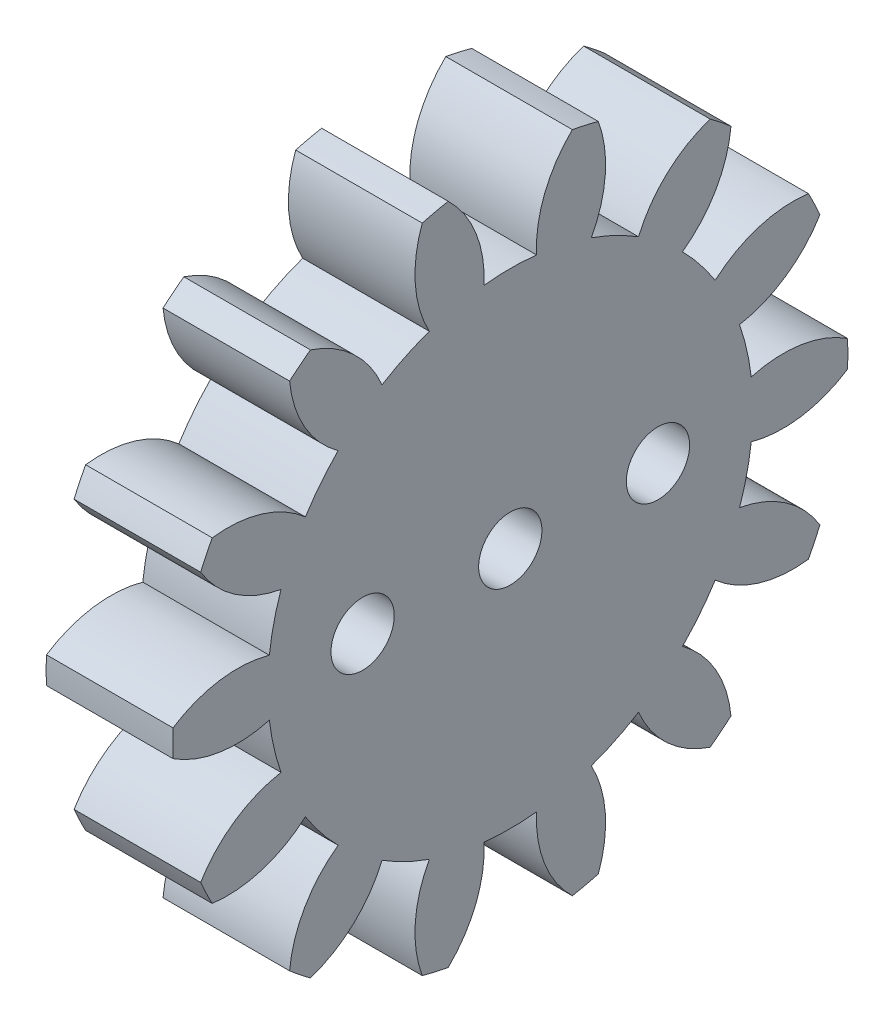
SolidWorks part; units mm, degrees
ref_plane "Plane1" through (0, 0, 0) normal (0, 0, 1) x (1, 0, 0)
ref_plane "Plane2" through (0, 0, 0) normal (0, 1, 0) x (1, 0, 0)
ref_plane "Plane3" through (0, 0, 0) normal (1, 0, 0) x (0, 0, -1)
sketch "HoldingSke" plane through (0, 0, 0) normal (0, 1, 0) x (1, 0, 0)
  line L0 (0, 0) -> (0.4851, -0.121)
  line L1 (-15, 0) -> (100, 0) construction
  line L2 (0, 0) -> (-2.1039, 2.3779)
  line L3 (0, 0) -> (-11.863, 4.5341)
  line L4 (0, 0) -> (8.3795, 2.0892)
  line L5 (0, 0) -> (-46.8476, -17.4728)
  line L6 (0, 0) -> (-4.9738, -3.3558)
  line L7 (-2.1039, 2.3779) -> (8.6586, 51.2059)
  line L8 (-76.2, 54.61) -> (-74.8, 54.61)
  line L9 (-67.7845, 28.3722) -> (-49.3413, 33.142)
  line L10 (-76.2, 71.12) -> (104.1128, 71.12)
  line L11 (0, 0) -> (-6, 0)
  line L12 (-76.2, 101.6) -> (-76.133, 101.6)
  line L13 (24.9733, 27.94) -> (52.9518, 28.4284)
  line L14 (24.9733, 27.94) -> (24.9743, 27.94)
  line L15 (24.9733, 27.94) -> (100.4006, 29.5858)
  line L16 (-63.627, -2) -> (-12.827, -2)
  circle A0 centre (0, 0) radius 4
  circle A1 centre (0, 0) radius 11.499
  circle A2 centre (0, 0) radius 37.5
  circle A3 centre (0, 0) radius 4
  dimension "MHD" = 22.998
  dimension "Hub_dia" = 75
  dimension "Bore" = 8
  dimension "MBD" = 8
  dimension "Num_teeth" = 14
  dimension "Pitch" = 0.5
  dimension "Overall_len" = 50
  dimension "Show_teeth" = 14
  dimension "Thickness" = 6
  dimension "OAL" = 50.0001
  dimension "T_dim" = 1.4
  dimension "Ap" = 14.5
  dimension "H" = 19.05
  dimension "Pitch_radius" = 180.3128
  dimension "Width" = 6
  dimension "Backlash" = 0.067
  dimension "Addendum_fac" = 1
  dimension "Dedendum_fac" = 1.25
  dimension "Clearance_fac" = 0.25
  dimension "Dedendum_add" = 0.001
  dimension "Module" = 2
sketch "BasProSke" plane through (0, 0, 0) normal (0, 1, 0) x (1, 0, 0)
  line L0 (-10, 0) -> (60, 0) construction
  line L1 (0, 0) -> (0, 16)
  line L2 (0, 0) -> (6, 0)
  line L3 (6, 0) -> (6, 16)
  line L4 (6, 16) -> (0, 16)
  dimension "Thickness" = 6
  dimension "Diameter" = 32
revolve "Base-Revolve" add sketch "BasProSke" angle 360 about L0
sketch "TooCutSke" plane through (0, 0, 0) normal (1, 0, 0) x (0, 0, -1)
  line L1 (0, 0) -> (0, 107) construction
  line L2 (0, 0) -> (-1.6846, 13.8983) construction
  line L3 (0, 0) -> (-6.1971, 27.1511) construction
  line L4 (-1.6846, 13.8983) -> (-3.0985, 13.5756) construction
  arc A0 (1.2433, 11.4316) -> (-1.2433, 11.4316) centre (0, 0) ccw
  arc A1 (2.9643, 15.7489) -> (-2.9643, 15.7489) centre (0, 0) ccw
  circle A2 centre (0, 0) radius 14 construction
  circle A3 centre (0, 0) radius 13.5541 construction
  arc A4 (-1.2433, 11.4316) -> (-2.9643, 15.7489) centre (-6.8366, 11.7035) ccw
  arc A5 (2.9643, 15.7489) -> (1.2433, 11.4316) centre (6.8366, 11.7035) ccw
  dimension "Root_dia" = 22.998
  dimension "Overcut_dia" = 32.0508
  dimension "Pitch_dia" = 28
  dimension "Base_dia" = 27.1081
  dimension "Flank_rad" = 5.6
  dimension "Half_ang" = 12.857
  dimension "Half_CT" = 1.4503
extrude "ToothCut" cut sketch "TooCutSke" along normal through all
fillet "Breaks" [suppressed] radius 0.04
fillet "RootFillets" [suppressed] radius 0.501
pattern_circular "TeethCuts" count 14 every 25.714 about axis through (-10, 0, 0) along (1, 0, 0) of "ToothCut", "RootFillets", "Breaks"
sketch "HubNeaOneSke" plane through (0, 0, 0) normal (-1, 0, 0) x (0, 0, 1)
  circle A0 centre (0, 0) radius 11.499
  dimension "Diameter" = 22.998
extrude "HubNearOne" [suppressed] add sketch "HubNeaOneSke" along normal blind 44.0001
sketch "HubNeaBotSke" plane through (0, 0, 0) normal (-1, 0, 0) x (0, 0, 1)
  circle A0 centre (0, 0) radius 11.499
  dimension "Diameter" = 22.998
extrude "HubNearBoth" [suppressed] add sketch "HubNeaBotSke" along normal blind 22
ref_plane "FarPln" through (6, 0, 0) normal (1, 0, 0) x (0, 0, -1)
sketch "HubFarSke" plane through (6, 0, 0) normal (1, 0, 0) x (0, 0, -1)
  circle A0 centre (0, 0) radius 11.499
  dimension "Diameter" = 22.998
extrude "HubFar" [suppressed] add sketch "HubFarSke" along normal blind 22
sketch "BorSke" plane through (0, 0, 0) normal (1, 0, 0) x (0, 0, -1)
  circle A0 centre (0, 0) radius 4
  dimension "Diameter" = 8
extrude "Bore" cut sketch "BorSke" along normal mid plane 100.0001
sketch "KeySke" plane through (0, 0, 0) normal (1, 0, 0) x (0, 0, -1)
  line L0 (-1.5, 0) -> (-1.5, 5.4)
  line L1 (-1.5, 5.4) -> (1.5, 5.4)
  line L2 (1.5, 5.4) -> (1.5, 0)
  line L3 (0, 0) -> (0, 34) construction
  line L4 (-1.5, 0) -> (1.5, 0)
  dimension "Offset" = 5.4
  dimension "Width" = 3
extrude "Keyway" [suppressed] cut sketch "KeySke" along normal mid plane 100.0001
pattern_circular "Keyway2" [suppressed] count 2 every 90 about axis through (-10, 0, 0) along (1, 0, 0)
sketch "Croquis1" plane through (6, 0, 0) normal (1, 0, 0) x (0, 0, -1)
  circle A0 centre (0, 0) radius 4
  circle A1 centre (0, 0) radius 1.5
extrude "Saliente-Extruir1" add sketch "Croquis1" against normal blind 6
sketch "Croquis2" plane through (6, 0, 0) normal (1, 0, 0) x (0, 0, -1)
  circle A0 centre (-7, 0) radius 1.5
  circle A1 centre (7, 0) radius 1.5
  circle A2 centre (0, 0) radius 1.5 construction
  dimension "D1" = 7
  dimension "D2" = 7
extrude "Cortar-Extruir1" cut sketch "Croquis2" against normal blind 6
equation "' \"Module@HoldingSke\" = 6.35"
equation "' \"Num_teeth@HoldingSke\" = 12"
equation "' \"Ap@HoldingSke\" =  20"
equation "' \"Ap@HoldingSke\" = 20"
equation "' \"Width@HoldingSke\" = 0.5 * 25.4"
equation "' \"Hub_dia@HoldingSke\"= 1 * 25.4"
equation "' \"Hub_dia@HoldingSke\" = 1 * 25.4"
equation "' \"Overall_len@HoldingSke\" = 1.0 * 25.4"
equation "' \"Bore@HoldingSke\" = 0.75 * 25.4"
equation "' \"T_dim@HoldingSke\" = 0.1 * 25.4"
equation "' \"Width@KeySke\" = 0.25 * 25.4"
equation "' \"Show_teeth@HoldingSke\" = 13"
equation "' \"Backlash@HoldingSke\" = 0.009 * 25.4"
equation "' \"Addendum_fac@HoldingSke\" = 1.0"
equation "' \"Dedendum_fac@HoldingSke\" = 1.25"
equation "' \"Dedendum_add@HoldingSke\" = 0.00005 * 25.4"
equation "' \"Clearance_fac@HoldingSke\" = 0.25"
equation "\"Pitch@HoldingSke\" = 1 / \"Module@HoldingSke\""
equation "\"Overcut_dia@TooCutSke\" = (\"Num_teeth@HoldingSke\" + 2 * \"Addendum_fac@HoldingSke\") / \"Pitch@HoldingSke\" + 0.002 * 25.4"
equation "\"Pitch_dia@TooCutSke\" = \"Num_teeth@HoldingSke\" / \"Pitch@HoldingSke\""
equation "\"Base_dia@TooCutSke\" = \"Num_teeth@HoldingSke\" / \"Pitch@HoldingSke\" * cos((\"Ap@HoldingSke\"  * 3.14159265 / 180))"
equation "\"Root_dia@TooCutSke\" = (\"Num_teeth@HoldingSke\" + 2) / \"Pitch@HoldingSke\" - 2 * (\"Addendum_fac@HoldingSke\" + \"Dedendum_fac@HoldingSke\") / \"Pitch@HoldingSke\" - \"Dedendum_add@HoldingSke\" * 2"
equation "\"Half_ang@TooCutSke\" = 180 / \"Num_teeth@HoldingSke\""
equation "\"Half_CT@TooCutSke\" = \"Num_teeth@HoldingSke\" / \"Pitch@HoldingSke\" * sin((3.14159265 / 2 / \"Num_teeth@HoldingSke\")) / 2 - 7 * \"Backlash@HoldingSke\" / 4"
equation "\"Flank_rad@TooCutSke\" = \"Num_teeth@HoldingSke\" / \"Pitch@HoldingSke\" / 5"
equation "\"Radius@RootFillets\" = \"Clearance_fac@HoldingSke\" / \"Pitch@HoldingSke\" + \"Dedendum_add@HoldingSke\""
equation "\"Break_rad@Breaks\" = 0.02 / \"Pitch@HoldingSke\""
equation "\"Thickness@HoldingSke\" = \"Width@HoldingSke\""
equation "\"OAL@HoldingSke\" = \"Thickness@HoldingSke\""
equation "\"MHD@HoldingSke\" = (\"Num_teeth@HoldingSke\" + 2) / \"Pitch@HoldingSke\" - 2 * (\"Addendum_fac@HoldingSke\" + \"Dedendum_fac@HoldingSke\")  / \"Pitch@HoldingSke\" - \"Dedendum_add@HoldingSke\" * 2"
equation "\"MBD@HoldingSke\" = (\"Num_teeth@HoldingSke\" + 2) / \"Pitch@HoldingSke\" - 2 * (\"Addendum_fac@HoldingSke\" + \"Dedendum_fac@HoldingSke\")  / \"Pitch@HoldingSke\" - \"Dedendum_add@HoldingSke\" * 2 - 0.002 * 25.4"
equation "\"MHD@HoldingSke\" = ((sgn( \"MHD@HoldingSke\" - \"Hub_dia@HoldingSke\" )-1)*( \"MHD@HoldingSke\" - \"Hub_dia@HoldingSke\" ))/-2+ \"Hub_dia@HoldingSke\""
equation "\"MBD@HoldingSke\" = ((sgn( \"MBD@HoldingSke\" - \"Bore@HoldingSke\" )-1)*( \"MBD@HoldingSke\" - \"Bore@HoldingSke\" ))/-2+ \"Bore@HoldingSke\""
equation "\"OAL@HoldingSke\" = ((sgn( \"OAL@HoldingSke\" - \"Overall_len@HoldingSke\" )+1)*( \"OAL@HoldingSke\" - \"Overall_len@HoldingSke\" ))/2 + \"Overall_len@HoldingSke\" + 0.000002 * 25.4"
equation "\"Num_teeth@TeethCuts\" = int( \"Show_teeth@HoldingSke\" ) + 1"
equation "\"Num_teeth@TeethCuts\" = ((sgn( \"Num_teeth@TeethCuts\" - \"Num_teeth@HoldingSke\" )-1)*( \"Num_teeth@TeethCuts\" - \"Num_teeth@HoldingSke\" ))/-2+ \"Num_teeth@HoldingSke\""
equation "\"Num_teeth@TeethCuts\" = ((sgn( \"Num_teeth@TeethCuts\" - 2.0)+1)*( \"Num_teeth@TeethCuts\" - 2.0))/2 +2.0"
equation "\"Angle@TeethCuts\" = 360.0 / \"Num_teeth@HoldingSke\""
equation "\"Diameter@BasProSke\" = (\"Num_teeth@HoldingSke\" + 2 * \"Addendum_fac@HoldingSke\") / \"Pitch@HoldingSke\""
equation "\"Thickness@BasProSke\"  = \"Thickness@HoldingSke\""
equation "' \"Fillet_rad@BasProSke\" =  \"Thickness@HoldingSke\" * 0.05"
equation "' \"Fillet_rad@BasProSke\" = \"Thickness@HoldingSke\" * 0.05"
equation "\"MHD@HoldingSke\" = ((sgn( \"MHD@HoldingSke\" - \"Root_dia@TooCutSke\" )-1)*( \"MHD@HoldingSke\" - \"Root_dia@TooCutSke\" ))/-2+ \"Root_dia@TooCutSke\""
equation "\"Diameter@HubNeaOneSke\" = \"MHD@HoldingSke\""
equation "\"Length@HubNearOne\" = \"OAL@HoldingSke\" - \"Thickness@BasProSke\""
equation "\"Diameter@HubNeaBotSke\" = \"MHD@HoldingSke\""
equation "\"Length@HubNearBoth\" = ( \"OAL@HoldingSke\" - \"Thickness@BasProSke\" ) / 2.0"
equation "\"Thickness@FarPln\" = \"Thickness@BasProSke\""
equation "\"Diameter@HubFarSke\" = \"MHD@HoldingSke\""
equation "\"Length@HubFar\" = ( \"OAL@HoldingSke\" - \"Thickness@BasProSke\" ) / 2.0"
equation "\"Diameter@BorSke\" = \"MBD@HoldingSke\""
equation "\"D1@Bore\" = \"OAL@HoldingSke\" * 2.0"
equation "\"D1@Keyway\" = \"OAL@HoldingSke\" * 2.0"
equation "\"Offset@KeySke\" = \"T_dim@HoldingSke\" + \"MBD@HoldingSke\" / 2.0"
